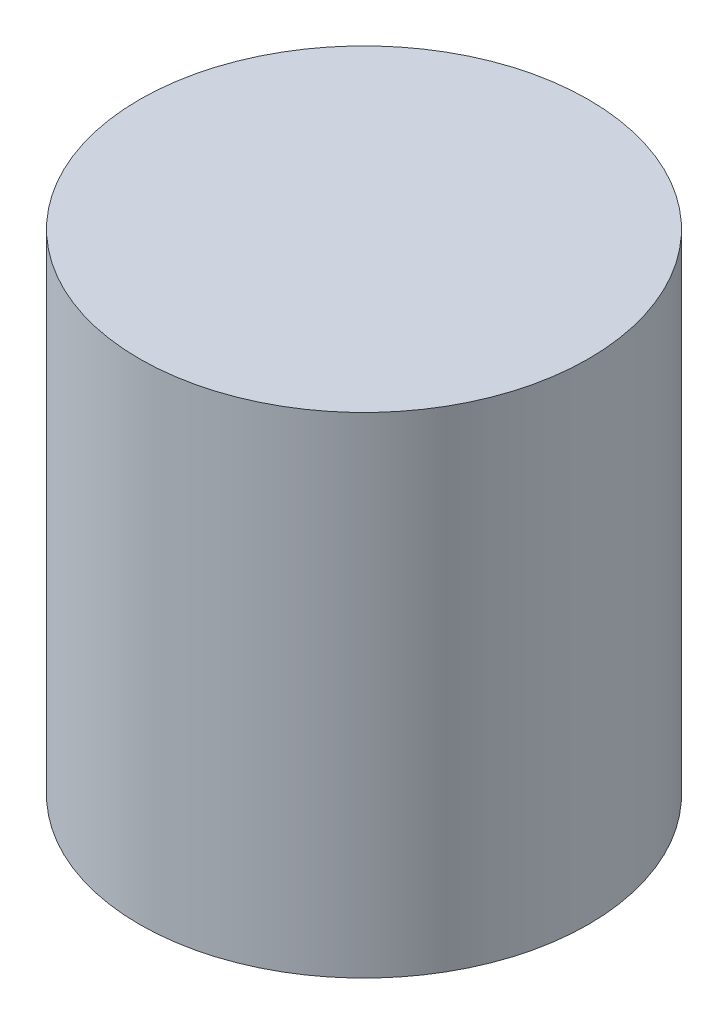
SolidWorks part; units mm, degrees
ref_plane "Front Plane" through (0, 0, 0) normal (0, 0, 1) x (1, 0, 0)
ref_plane "Top Plane" through (0, 0, 0) normal (0, 1, 0) x (1, 0, 0)
ref_plane "Right Plane" through (0, 0, 0) normal (1, 0, 0) x (0, 0, -1)
sketch "Sketch1" plane through (0, 0, 0) normal (0, 1, 0) x (1, 0, 0)
  circle A0 centre (0, 0) radius 5.5
  dimension "D1" = 11
extrude "Boss-Extrude1" add sketch "Sketch1" along normal blind 12
